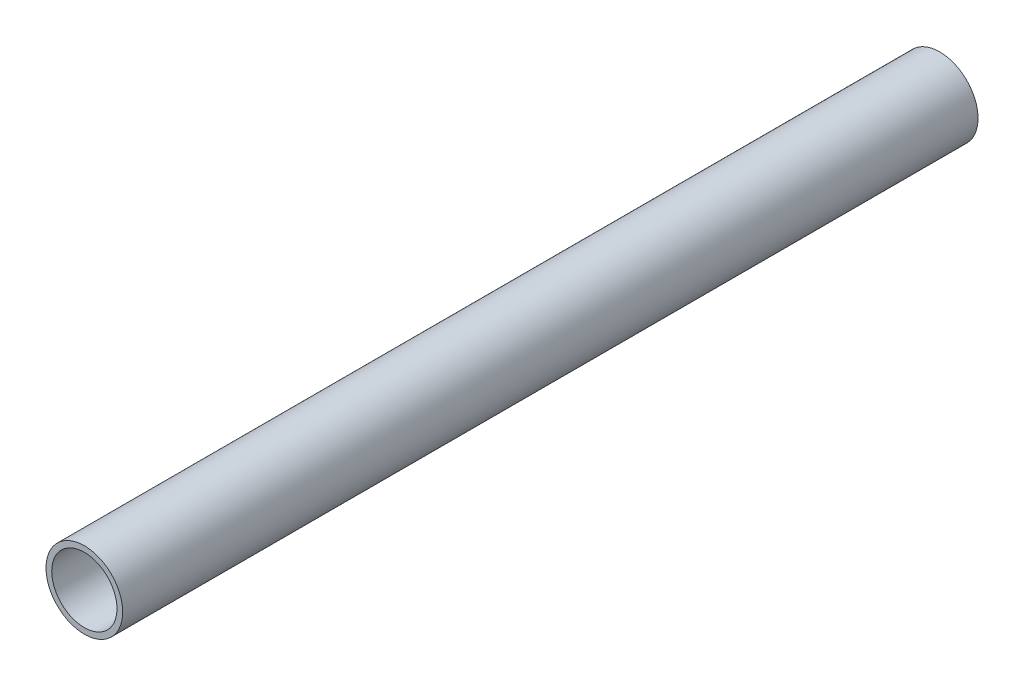
SolidWorks part; units mm, degrees
ref_plane "Front Plane" through (0, 0, 0) normal (0, 0, 1) x (1, 0, 0)
ref_plane "Top Plane" through (0, 0, 0) normal (0, 1, 0) x (1, 0, 0)
ref_plane "Right Plane" through (0, 0, 0) normal (1, 0, 0) x (0, 0, -1)
sketch "Sketch1" plane through (0, 0, 0) normal (0, 0, 1) x (1, 0, 0)
  circle A0 centre (0, 0) radius 13.45
  dimension "D1" = 26.9
extrude "Extrude-Thin1" add sketch "Sketch1" along normal mid plane 300 thin thin type one direction reverse wall 2
